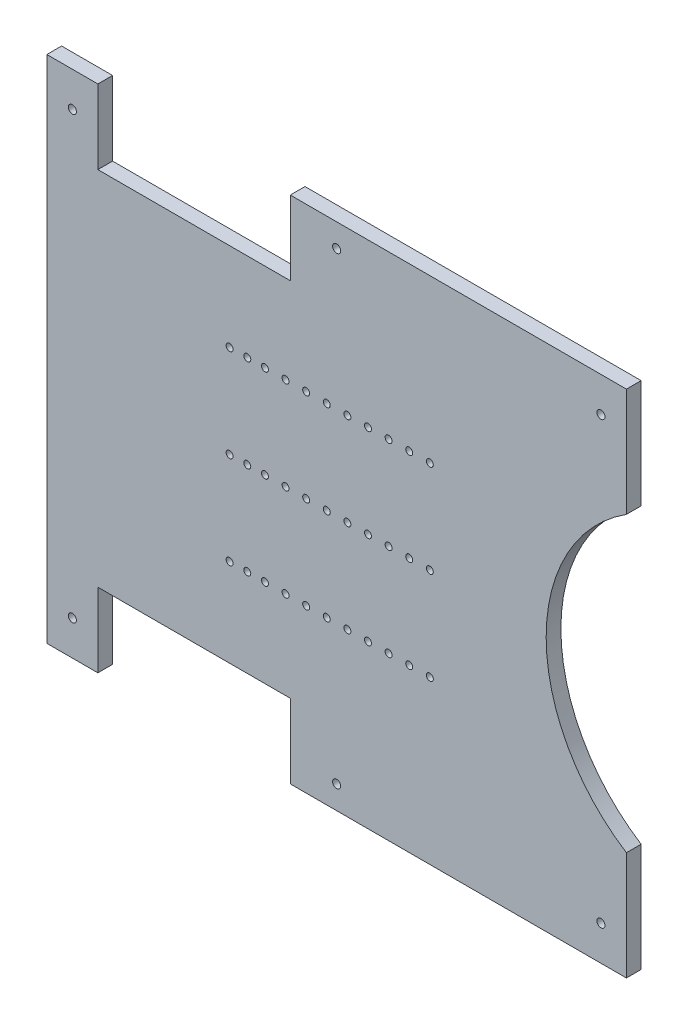
SolidWorks part; units mm, degrees
ref_plane "Front Plane" through (0, 0, 0) normal (0, 0, 1) x (1, 0, 0)
ref_plane "Top Plane" through (0, 0, 0) normal (0, 1, 0) x (1, 0, 0)
ref_plane "Right Plane" through (0, 0, 0) normal (1, 0, 0) x (0, 0, -1)
sketch "Sketch1" plane through (0, 0, 0) normal (0, 0, 1) x (1, 0, 0)
  line L3 (119.6098, 110) -> (97.6098, 110)
  line L8 (-108.3902, 110) -> (-108.3902, 78)
  line L9 (-108.3902, 78) -> (-25.3902, 78)
  line L10 (-25.3902, 110) -> (-25.3902, 78)
  line L14 (-5.3902, 100) -> (-5.3902, -38) construction
  line L21 (-108.3902, 110) -> (-130.3902, 110)
  line L22 (14.6098, 110) -> (-25.3902, 110)
  line L25 (0, 0) -> (-110, 0) construction
  line L58 (-130, 0) -> (-186.6797, 0) construction
  line L60 (119.6098, 110) -> (119.6098, 63.2)
  line L61 (14.6098, -110) -> (-25.3902, -110)
  line L62 (-108.3902, -110) -> (-130.3902, -110)
  line L66 (-25.3902, -110) -> (-25.3902, -78)
  line L67 (-108.3902, -78) -> (-25.3902, -78)
  line L68 (-108.3902, -110) -> (-108.3902, -78)
  line L69 (119.6098, -110) -> (97.6098, -110)
  line L71 (119.6098, -63.2) -> (119.6098, -110)
  line L72 (-130.3902, 110) -> (-130.3902, -110)
  line L73 (14.6098, 110) -> (97.6098, 110)
  line L75 (14.6098, -110) -> (97.6098, -110)
  circle A2 centre (-119.3902, 95) radius 1.7525
  circle A3 centre (108.6098, 95) radius 1.7525
  circle A7 centre (-5.3902, 100) radius 1.7525
  circle A8 centre (-5.3902, -100) radius 1.7525
  circle A9 centre (108.6098, -95) radius 1.7525
  circle A10 centre (-119.3902, -95) radius 1.7525
  arc A12 (119.6098, -63.2) -> (119.6098, 63.2) centre (159.9925, 0) cw
  circle A13 centre (-36.3118, 40) radius 1.5
  circle A14 centre (-36.3118, 0) radius 1.5
  circle A15 centre (-36.3118, -40) radius 1.5
  circle A16 centre (-27.4218, -40) radius 1.5
  circle A17 centre (-27.4218, 0) radius 1.5
  circle A18 centre (-27.4218, 40) radius 1.5
  circle A19 centre (-18.5318, -40) radius 1.5
  circle A20 centre (-18.5318, 0) radius 1.5
  circle A21 centre (-18.5318, 40) radius 1.5
  circle A22 centre (-9.6418, -40) radius 1.5
  circle A23 centre (-9.6418, 0) radius 1.5
  circle A24 centre (-9.6418, 40) radius 1.5
  circle A25 centre (-0.7518, -40) radius 1.5
  circle A26 centre (-0.7518, 0) radius 1.5
  circle A27 centre (-0.7518, 40) radius 1.5
  circle A28 centre (8.1382, -40) radius 1.5
  circle A29 centre (8.1382, 0) radius 1.5
  circle A30 centre (8.1382, 40) radius 1.5
  circle A31 centre (17.0282, -40) radius 1.5
  circle A32 centre (17.0282, 0) radius 1.5
  circle A33 centre (17.0282, 40) radius 1.5
  circle A34 centre (25.9182, -40) radius 1.5
  circle A35 centre (25.9182, 0) radius 1.5
  circle A36 centre (25.9182, 40) radius 1.5
  circle A37 centre (34.8082, -40) radius 1.5
  circle A38 centre (34.8082, 0) radius 1.5
  circle A39 centre (34.8082, 40) radius 1.5
  circle A40 centre (-43.9318, 0) radius 1.5
  circle A41 centre (-43.9318, -40) radius 1.5
  circle A42 centre (-43.9318, 40) radius 1.5
  circle A43 centre (-51.5518, 0) radius 1.5
  circle A44 centre (-51.5518, -40) radius 1.5
  circle A45 centre (-51.5518, 40) radius 1.5
  point P0 (0, 0)
  point P20 (-130, 0)
  point P21 (119.2196, 0)
  dimension "D12" = 75
  dimension "D13" = 3.505
  dimension "D16" = 3.505
  dimension "D17" = 20
  dimension "D24" = 3.505
  dimension "D5" = 40
  dimension "D6" = 11
  dimension "D14" = 3
  dimension "D20" = 3
  dimension "D1" = 250
  dimension "D3" = 83
  dimension "D4" = 32
  dimension "D10" = 110
  dimension "D15" = 15
  dimension "D18" = 10
  dimension "D19" = 40
  dimension "D21" = 9
  dimension "D23" = 15
  dimension "D25" = 3
extrude "Boss-Extrude1" add sketch "Sketch1" along normal blind 6.35
